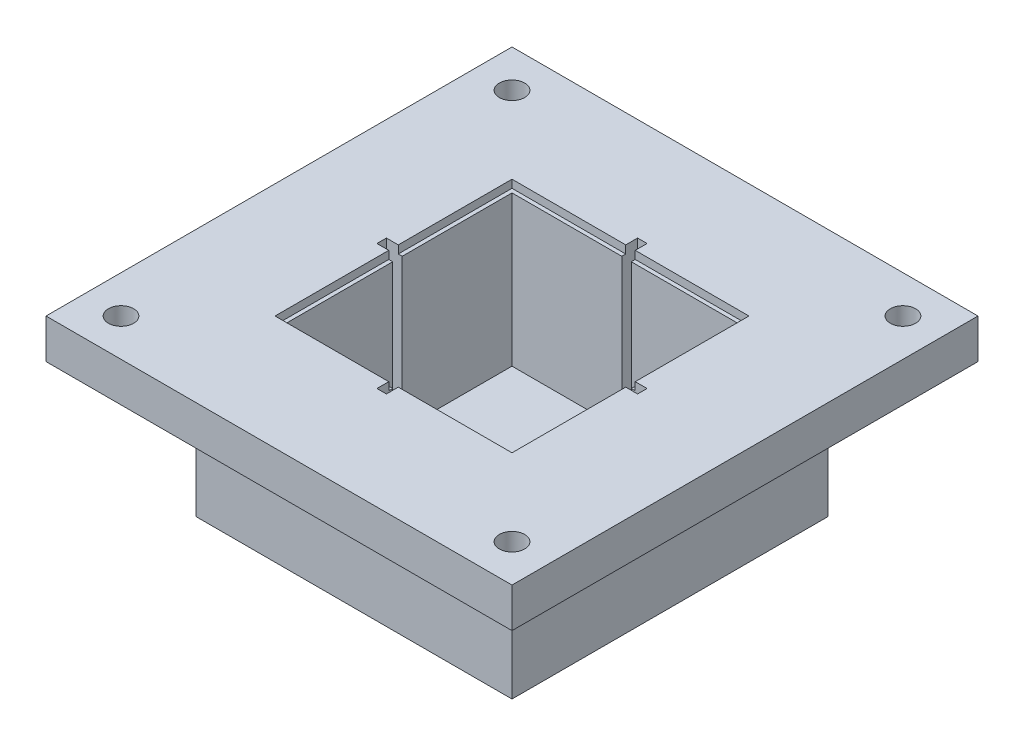
SolidWorks part; units mm, degrees
ref_plane "Alzado" through (0, 0, 0) normal (0, 0, 1) x (1, 0, 0)
ref_plane "Planta" through (0, 0, 0) normal (0, 1, 0) x (1, 0, 0)
ref_plane "Vista lateral" through (0, 0, 0) normal (1, 0, 0) x (0, 0, -1)
sketch "Croquis1" plane through (0, 0, 0) normal (0, 1, 0) x (1, 0, 0)
  line L1 (0, 0) -> (40, 0)
  line L2 (0, 0) -> (0, 40)
  line L3 (0, 40) -> (40, 40)
  line L4 (40, 0) -> (40, 40)
  dimension "D1" = 40
extrude "Saliente-Extruir1" add sketch "Croquis1" along normal blind 2
sketch "Croquis2" plane through (0, 2, 0) normal (0, 1, 0) x (1, 0, 0)
  line L0 (5.5, 34.5) -> (5.5, 5.5)
  line L1 (5.5, 5.5) -> (34.5, 5.5)
  line L2 (34.5, 5.5) -> (34.5, 34.5)
  line L3 (34.5, 34.5) -> (5.5, 34.5)
  line L4 (0, 40) -> (0, 0)
  line L5 (0, 0) -> (40, 0)
  line L6 (40, 0) -> (40, 40)
  line L7 (40, 40) -> (0, 40)
  line L8 (0, 40) -> (0, 0)
  line L9 (0, 0) -> (40, 0)
  line L10 (40, 0) -> (40, 40)
  line L11 (40, 40) -> (0, 40)
  dimension "D1" = 0
  dimension "D2" = 5.5
extrude "Saliente-Extruir2" add sketch "Croquis2" along normal blind 15
sketch "Croquis3" plane through (0, 17, 0) normal (0, 1, 0) x (1, 0, 0)
  line L0 (5.5, 5.5) -> (34.5, 5.5) construction
  line L1 (34.5, 5.5) -> (34.5, 34.5) construction
  line L2 (34.5, 34.5) -> (5.5, 34.5) construction
  line L3 (5.5, 34.5) -> (5.5, 5.5) construction
  line L4 (5.5, 5.5) -> (34.5, 5.5)
  line L5 (34.5, 5.5) -> (34.5, 34.5)
  line L6 (34.5, 34.5) -> (5.5, 34.5)
  line L7 (5.5, 34.5) -> (5.5, 5.5)
  line L8 (-9.5, -9.5) -> (49.5, -9.5)
  line L9 (49.5, -9.5) -> (49.5, 49.5)
  line L10 (49.5, 49.5) -> (-9.5, 49.5)
  line L11 (-9.5, 49.5) -> (-9.5, -9.5)
  dimension "D1" = 15
extrude "Saliente-Extruir3" add sketch "Croquis3" along normal blind 5
sketch "Croquis4" plane through (0, 22, 0) normal (0, 1, 0) x (1, 0, 0)
  line L0 (20, 3.5) -> (20, 49.5) construction
  line L2 (19.4, 5.5) -> (19.4, 3.5)
  line L3 (19.4, 3.5) -> (20.6, 3.5)
  line L4 (34.5, 5.5) -> (34.5, 34.5)
  line L5 (34.5, 34.5) -> (5.5, 34.5)
  line L6 (5.5, 34.5) -> (5.5, 5.5)
  line L7 (5.5, 5.5) -> (34.5, 5.5)
  line L8 (34.5, 5.5) -> (34.5, 19.4)
  line L9 (34.5, 34.5) -> (20.6, 34.5)
  line L10 (5.5, 34.5) -> (5.5, 20.6)
  line L11 (5.5, 5.5) -> (19.4, 5.5)
  line L12 (20.6, 5.5) -> (20.6, 3.5)
  line L13 (49.5, 49.5) -> (-9.5, 49.5) construction
  line L14 (20.6, 5.5) -> (34.5, 5.5)
  line L15 (-9.5, 20) -> (49.5, 20) construction
  line L16 (-9.5, 49.5) -> (-9.5, -9.5) construction
  line L17 (49.5, -9.5) -> (49.5, 49.5) construction
  line L18 (34.5, 20.6) -> (34.5, 34.5)
  line L19 (34.5, 19.4) -> (36.5, 19.4)
  line L21 (34.5, 20.6) -> (36.5, 20.6)
  line L22 (36.5, 19.4) -> (36.5, 20.6)
  line L23 (5.5, 19.4) -> (3.5, 19.4)
  line L24 (3.5, 19.4) -> (3.5, 20.6)
  line L25 (5.5, 20.6) -> (3.5, 20.6)
  line L26 (20.6, 34.5) -> (20.6, 36.5)
  line L27 (19.4, 36.5) -> (20.6, 36.5)
  line L28 (19.4, 34.5) -> (19.4, 36.5)
  line L29 (5.5, 19.4) -> (5.5, 5.5)
  line L30 (19.4, 34.5) -> (5.5, 34.5)
  point P22 (36.5, 20)
  dimension "D2" = 1.2
  dimension "D3" = 2
  dimension "D4" = 2
  dimension "D5" = 1.2
  dimension "D1" = 0
extrude "Cortar-Extruir1" cut sketch "Croquis4" against normal up to surface (20 mm away) up to face at (20, 2, -20)
sketch "Croquis5" plane through (0, 17, 0) normal (0, -1, 0) x (1, 0, 0)
  line L0 (0, 0) -> (40, -40) construction
  line L1 (0, 0) -> (-9.5, 9.5) construction
  line L2 (20, -20) -> (40, 0) construction
  circle A0 centre (-4.75, 4.75) radius 1.6
  circle A4 centre (44.75, 4.75) radius 1.6
  circle A5 centre (44.75, -44.75) radius 1.6
  circle A6 centre (-4.75, -44.75) radius 1.6
  dimension "D1" = 3.2
  dimension "D2" = 4
extrude "Cortar-Extruir2" cut sketch "Croquis5" against normal blind 5
sketch "Croquis6" plane through (0, 22, 0) normal (0, 1, 0) x (1, 0, 0)
  line L0 (-9.5, 49.5) -> (49.5, -9.5) construction
  line L2 (35, 5) -> (5, 5)
  line L3 (35, 5) -> (35, 35)
  line L4 (35, 35) -> (5, 35)
  line L5 (5, 5) -> (5, 35)
  line L6 (35, 5) -> (5, 35) construction
  line L7 (35, 35) -> (5, 5) construction
  point P4 (20, 20)
  dimension "D1" = 30
extrude "Cortar-Extruir3" cut sketch "Croquis6" against normal blind 1
sketch "Croquis7" plane through (0, 2, 0) normal (0, 1, 0) x (1, 0, 0)
  line L1 (34.5, 5.5) -> (31.5, 5.5)
  line L2 (34.5, 5.5) -> (34.5, 8.5)
  line L3 (34.5, 8.5) -> (31.5, 8.5)
  line L4 (31.5, 5.5) -> (31.5, 8.5)
  dimension "D1" = 3
extrude "Cortar-Extruir4" cut sketch "Croquis7" against normal blind 5
